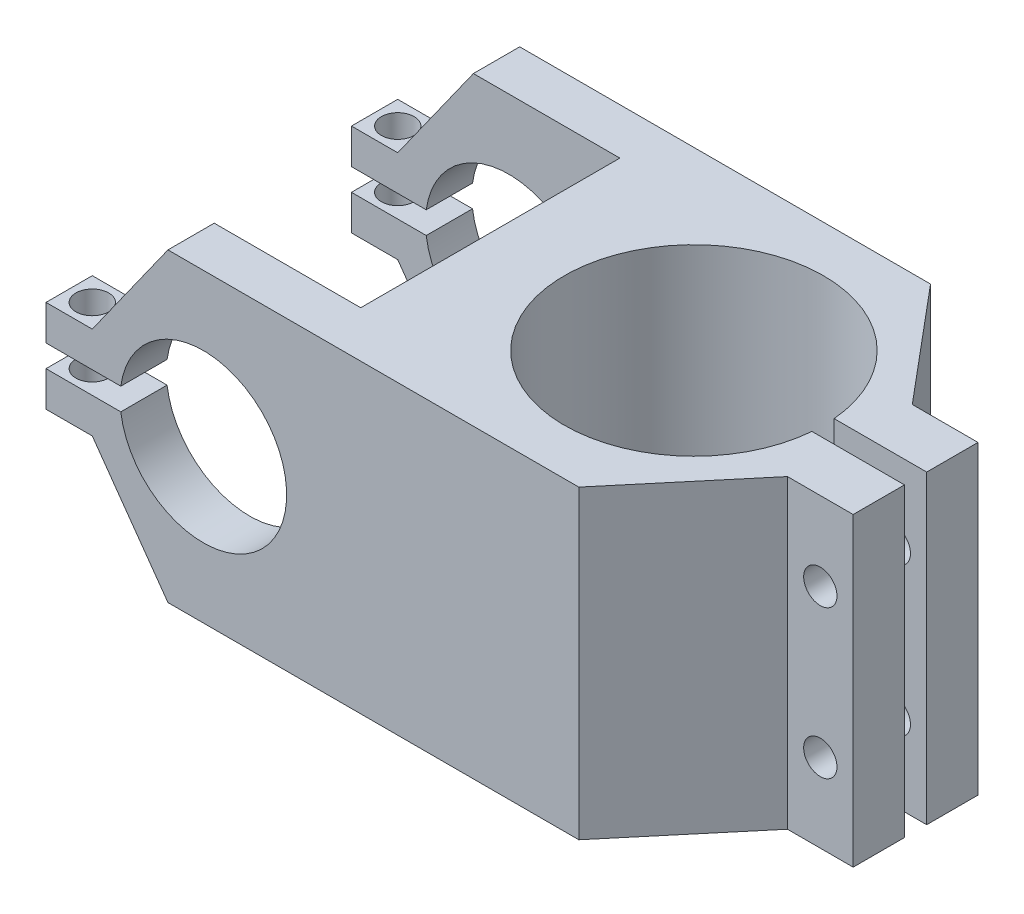
SolidWorks part; units mm, degrees
ref_plane "Front Plane" through (0, 0, 0) normal (0, 0, 1) x (1, 0, 0)
ref_plane "Top Plane" through (0, 0, 0) normal (0, 1, 0) x (1, 0, 0)
ref_plane "Right Plane" through (0, 0, 0) normal (1, 0, 0) x (0, 0, -1)
sketch "Sketch1" plane through (0, 0, 0) normal (0, 1, 0) x (1, 0, 0)
  line L0 (0, 0) -> (-66.726, 0) construction
  line L1 (-121.1334, 24.13) -> (-48.0271, 24.13)
  line L2 (-48.0271, 24.13) -> (-34.9656, 8.564)
  line L3 (-34.9656, 8.564) -> (-25.9488, 8.564)
  line L4 (-25.9488, 8.564) -> (-25.9488, 1.524)
  line L5 (-25.9488, 1.524) -> (-38.6488, 1.524)
  line L6 (-25.9488, -1.524) -> (-38.6488, -1.524)
  line L7 (-25.9488, -8.564) -> (-25.9488, -1.524)
  line L8 (-34.9656, -8.564) -> (-25.9488, -8.564)
  line L9 (-48.0271, -24.13) -> (-34.9656, -8.564)
  line L10 (-121.1334, -24.13) -> (-48.0271, -24.13)
  line L11 (-121.1334, 24.13) -> (-121.1334, 17.78)
  line L12 (-121.1334, 17.78) -> (-84.3034, 17.78)
  line L16 (-84.3034, 17.78) -> (-84.3034, -17.78)
  line L17 (-121.1334, -17.78) -> (-84.3034, -17.78)
  line L18 (-121.1334, -24.13) -> (-121.1334, -17.78)
  arc A0 (-38.6488, 1.524) -> (-38.6488, -1.524) centre (-56.3634, 0) ccw
  point P20 (-84.3034, 0)
  point P21 (-53.8234, 0)
  dimension "D3" = 1.524
  dimension "D8" = 17.78
  dimension "D11" = 27.94
  dimension "D1" = 24.13
  dimension "D2" = 12.7
  dimension "D4" = 20.32
  dimension "D5" = 50
  dimension "D6" = 9.0168
  dimension "D7" = 7.04
  dimension "D9" = 6.35
  dimension "D10" = 36.83
  dimension "D12" = 73.1063
  dimension "D13" = 95.1846
extrude "Boss-Extrude1" add sketch "Sketch1" along normal blind 41.91
ref_plane "Plane1" through (0, 0, 24.13) normal (0, 0, 1) x (1, 0, 0)
sketch "Sketch2" plane through (0, 0, 24.13) normal (0, 0, 1) x (1, 0, 0)
  line L0 (-121.1334, 20.955) -> (-99.5434, 20.955) construction
  line L1 (-121.1334, 41.91) -> (-121.1334, 0) construction
  circle A0 centre (-99.5434, 20.955) radius 11.43
  dimension "D1" = 21.59
extrude "Cut-Extrude1" cut sketch "Sketch2" against normal blind 56.388
sketch "Sketch3" plane through (0, 0, 24.13) normal (0, 0, 1) x (1, 0, 0)
  line L0 (-121.1334, 20.955) -> (-93.095, 20.955) construction
  line L25 (-121.1334, 41.91) -> (-121.1334, 0) construction
  line L26 (-121.1334, 22.479) -> (-100.0687, 22.479)
  line L27 (-100.0687, 22.479) -> (-100.0687, 19.431)
  line L28 (-100.0687, 19.431) -> (-121.1334, 19.431)
  line L29 (-121.1334, 19.431) -> (-121.1334, 22.479)
  line L30 (-121.1334, 22.479) -> (-121.1334, 27.305)
  line L31 (-121.1334, 27.305) -> (-114.7834, 27.305)
  line L32 (-114.7834, 27.305) -> (-104.401, 41.91)
  line L33 (-121.1334, 41.91) -> (-48.0271, 41.91) construction
  line L34 (-104.401, 41.91) -> (-121.1334, 41.91)
  line L35 (-121.1334, 41.91) -> (-121.1334, 27.305)
  line L36 (-121.1334, 0) -> (-121.1334, 14.605)
  line L37 (-104.401, 0) -> (-121.1334, 0)
  line L38 (-114.7834, 14.605) -> (-104.401, 0)
  line L39 (-121.1334, 14.605) -> (-114.7834, 14.605)
  point P19 (-102.1519, 44.45)
  point P20 (-114.7834, 27.305)
  point P21 (-104.401, 44.45)
  dimension "D1" = 1.524
  dimension "D2" = 1.524
  dimension "D3" = 6.35
  dimension "D4" = 12.7
extrude "Cut-Extrude3" cut sketch "Sketch3" against normal blind 56.388 contours L39 L36 L37 L38 | L34 L35 L31 L32 | L0 L29 L28 L27 | L29 L0 L27 L26
ref_plane "Plane2" through (0, 27.305, 0) normal (0, 1, 0) x (1, 0, 0)
sketch "Sketch4" plane through (0, 27.305, 0) normal (0, 1, 0) x (1, 0, 0)
  circle A0 centre (-117.9584, 20.955) radius 2.25
  circle A1 centre (-117.9584, -20.955) radius 2.25
  point P4 (-117.9584, -20.955)
  dimension "D1" = 4.5
extrude "Cut-Extrude4" cut sketch "Sketch4" against normal blind 56.388
ref_plane "Plane3" through (0, 0, 8.564) normal (0, 0, 1) x (1, 0, 0)
sketch "Sketch5" plane through (0, 0, 8.564) normal (0, 0, 1) x (1, 0, 0)
  line L0 (-25.9488, 20.955) -> (-31.4137, 20.955) construction
  line L1 (-25.9488, 41.91) -> (-25.9488, 0) construction
  circle A0 centre (-30.4572, 31.115) radius 2.286
  circle A1 centre (-30.4572, 10.795) radius 2.286
  dimension "D1" = 10.16
extrude "Cut-Extrude5" cut sketch "Sketch5" against normal blind 56.388
